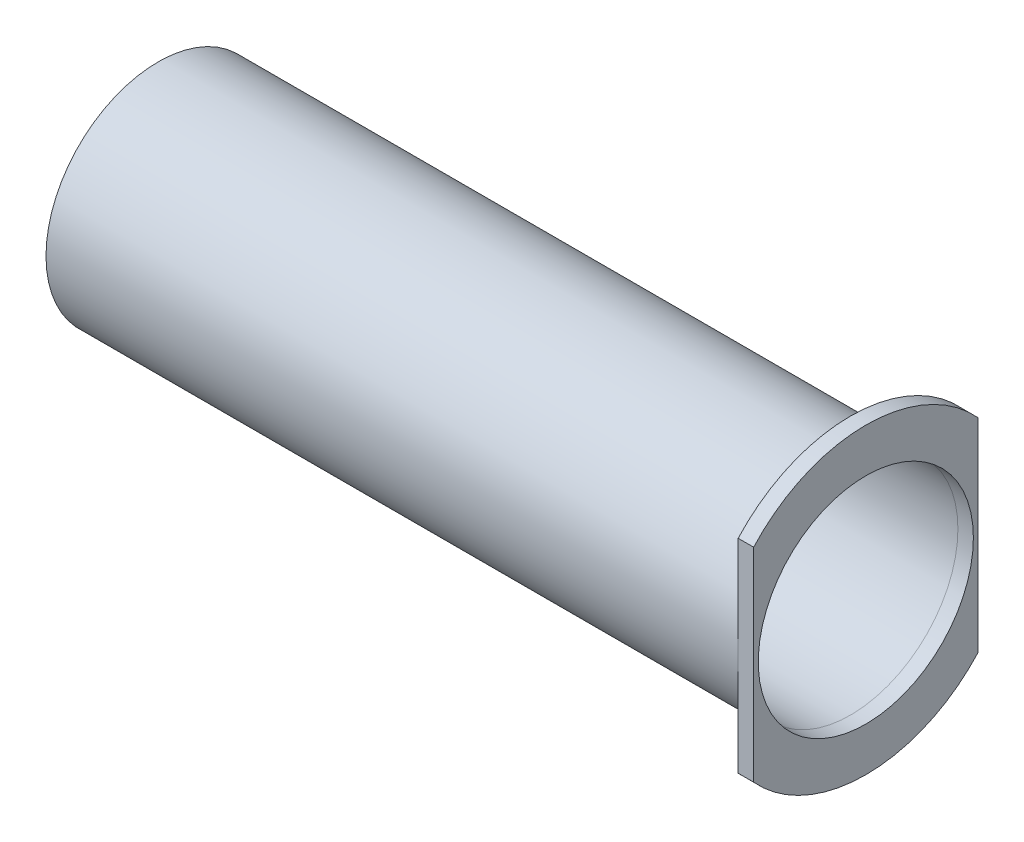
SolidWorks part; units mm, degrees
ref_plane "Płaszczyzna przednia" through (0, 0, 0) normal (0, 0, 1) x (1, 0, 0)
ref_plane "Płaszczyzna górna" through (0, 0, 0) normal (0, 1, 0) x (1, 0, 0)
ref_plane "Płaszczyzna prawa" through (0, 0, 0) normal (1, 0, 0) x (0, 0, -1)
sketch "Sketch1" plane through (0, 0, 0) normal (0, 0, 1) x (1, 0, 0)
  line L0 (-73.8947, 0) -> (76.1053, 0)
  line L1 (-73.8947, 24.31) -> (76.1053, 24.31)
  line L6 (-73.8947, 24.31) -> (-73.8947, 4.825)
  line L7 (76.1053, 24.31) -> (76.1053, 0)
  line L8 (-73.8947, 4.825) -> (-78.8947, 4.825)
  line L9 (-78.8947, 4.825) -> (-78.8947, 0)
  line L10 (-78.8947, 0) -> (-73.8947, 0)
  dimension "D1" = 150
  dimension "D2" = 24.31
  dimension "D3" = 19.485
  dimension "D4" = 5
revolve "Revolve2" add sketch "Sketch1" angle 360 about L0
sketch "Sketch2" plane through (-78.8947, 0, 0) normal (-1, 0, 0) x (0, 0, 1)
  circle A0 centre (0, 0) radius 3.825
  circle A1 centre (0, 0) radius 4.825 construction
  dimension "D1" = 1
extrude "Cut-Extrude1" cut sketch "Sketch2" against normal blind 260 and the other way blind 45
sketch "Sketch3" plane through (76.1053, 0, 0) normal (1, 0, 0) x (0, 0, -1)
  circle A0 centre (0, 0) radius 23.31
  circle A1 centre (0, 0) radius 24.31 construction
  dimension "D1" = 1
extrude "Cut-Extrude2" cut sketch "Sketch3" along a picked direction on the side against the normal blind 149
sketch "Sketch4" plane through (76.1053, 0, 0) normal (1, 0, 0) x (0, 0, -1)
  line L0 (24.31, 0) -> (24.31, 22.0494)
  line L1 (24.31, 22.0494) -> (24.31, -22.0494)
  line L2 (-24.31, 0) -> (-24.31, 22.0494)
  line L3 (-24.31, 22.0494) -> (-24.31, -22.0494)
  circle A0 centre (0, 0) radius 32.82
  circle A1 centre (0, 0) radius 24.31 construction
  circle A2 centre (0, 0) radius 23.31
  circle M1 centre (0, 0) radius 23.31
  circle M2 centre (0, 0) radius 24.31
  dimension "D1" = 65.64
extrude "Boss-Extrude1" add sketch "Sketch4" along normal blind 3.35 separate body contours L0 A0 L2 M2 | L3 A0 L1 M2 | M2 M1
